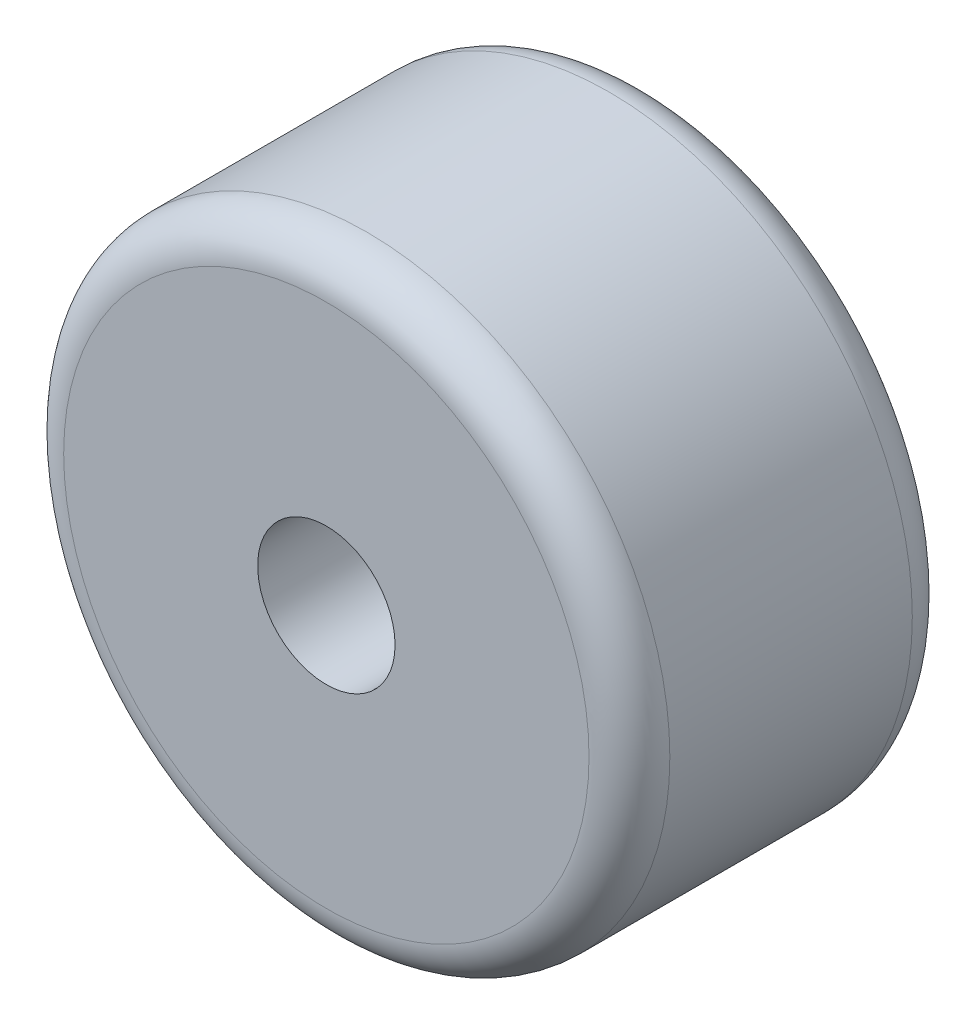
SolidWorks part; units mm, degrees
ref_plane "Front Plane" through (0, 0, 0) normal (0, 0, 1) x (1, 0, 0)
ref_plane "Top Plane" through (0, 0, 0) normal (0, 1, 0) x (1, 0, 0)
ref_plane "Right Plane" through (0, 0, 0) normal (1, 0, 0) x (0, 0, -1)
sketch "Sketch1" plane through (0, 0, 0) normal (0, 0, 1) x (1, 0, 0)
  circle A0 centre (0, 0) radius 7.5
  circle A1 centre (0, 0) radius 1.7
  dimension "D1" = 15
  dimension "D2" = 3.4
extrude "Boss-Extrude1" add sketch "Sketch1" along normal blind 8
fillet "Fillet1" radius 1 2 edges at (7.5, 0, 0) (7.5, 0, 8)
